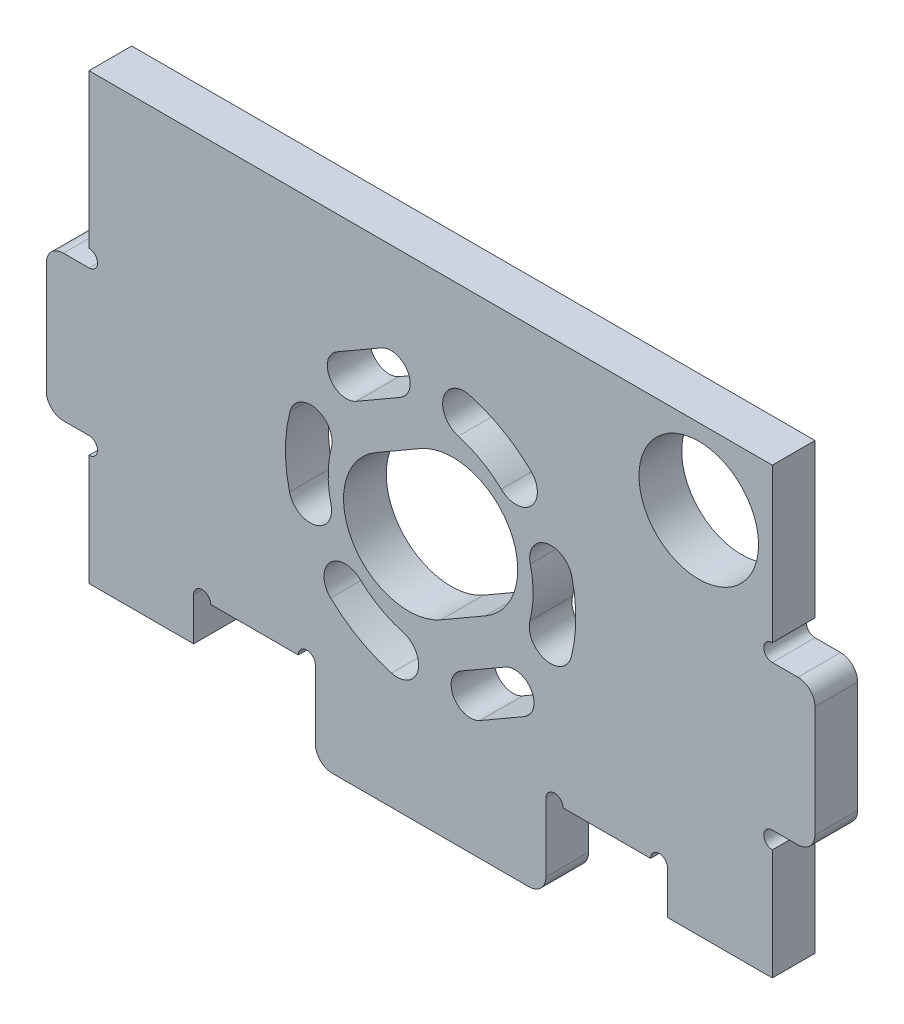
SolidWorks part; units mm, degrees
ref_plane "정면" through (0, 0, 0) normal (0, 0, 1) x (1, 0, 0)
ref_plane "윗면" through (0, 0, 0) normal (0, 1, 0) x (1, 0, 0)
ref_plane "우측면" through (0, 0, 0) normal (1, 0, 0) x (0, 0, -1)
sketch "스케치1" plane through (0, 0, 0) normal (0, 0, 1) x (1, 0, 0)
  line L0 (-5.1962, 22.5) -> (0, 25.5) construction
  line L1 (-42.5981, 51) -> (37.4019, 51)
  line L2 (-42.5981, 51) -> (-42.5981, -1)
  line L3 (-42.5981, -1) -> (37.4019, -1)
  line L4 (37.4019, 51) -> (37.4019, -1)
  line L5 (-8.9962, 29.0818) -> (-3.8, 32.0818)
  line L6 (-1.3962, 15.9182) -> (3.8, 18.9182)
  line L7 (-9.8481, 36.5574) -> (-2.5981, 24) construction
  line L8 (-2.5981, 24) -> (4.6519, 11.4426) construction
  line L9 (-2.5981, 24) -> (4.6519, 36.5574) construction
  line L10 (-2.5981, 24) -> (11.9019, 24) construction
  line L11 (-2.5981, 24) -> (9.9593, 31.25) construction
  arc A0 (-8.9962, 29.0818) -> (-1.3962, 15.9182) centre (-5.1962, 22.5) ccw
  circle A1 centre (-2.5981, 24) radius 14.5 construction
  arc A2 (1.3092, 37.9636) -> (7.3956, 34.506) centre (-2.5981, 24) cw construction
  arc A3 (3.8, 18.9182) -> (-3.8, 32.0818) centre (0, 25.5) ccw
  arc A4 (9.1187, 36.3174) -> (1.9829, 40.3712) centre (-2.5981, 24) ccw
  arc A5 (5.6726, 32.6946) -> (0.6355, 35.5561) centre (-2.5981, 24) ccw
  arc A6 (5.6726, 32.6946) -> (9.1187, 36.3174) centre (7.3956, 34.506) ccw
  arc A7 (1.9829, 40.3712) -> (0.6355, 35.5561) centre (1.3092, 37.9636) ccw
  arc A8 (11.4484, 20.402) -> (11.4972, 27.4018) centre (-2.5981, 24) ccw construction
  arc A9 (13.9275, 27.9883) -> (13.8702, 19.7816) centre (-2.5981, 24) cw
  arc A10 (9.067, 26.8153) -> (9.0266, 21.0223) centre (-2.5981, 24) cw
  arc A11 (9.067, 26.8153) -> (13.9275, 27.9883) centre (11.4972, 27.4018) cw
  arc A12 (13.8702, 19.7816) -> (9.0266, 21.0223) centre (11.4484, 20.402) cw
  arc A13 (-6.5053, 10.0364) -> (-12.5918, 13.494) centre (-2.5981, 24) cw construction
  arc A14 (-14.3148, 11.6826) -> (-7.179, 7.6288) centre (-2.5981, 24) ccw
  arc A15 (-10.8687, 15.3054) -> (-5.8317, 12.4439) centre (-2.5981, 24) ccw
  arc A16 (-10.8687, 15.3054) -> (-14.3148, 11.6826) centre (-12.5918, 13.494) ccw
  arc A17 (-7.179, 7.6288) -> (-5.8317, 12.4439) centre (-6.5053, 10.0364) ccw
  arc A18 (-16.6446, 27.598) -> (-16.6934, 20.5982) centre (-2.5981, 24) ccw construction
  arc A19 (-19.1236, 20.0117) -> (-19.0664, 28.2184) centre (-2.5981, 24) cw
  arc A20 (-14.2632, 21.1847) -> (-14.2228, 26.9777) centre (-2.5981, 24) cw
  arc A21 (-14.2632, 21.1847) -> (-19.1236, 20.0117) centre (-16.6934, 20.5982) cw
  arc A22 (-19.0664, 28.2184) -> (-14.2228, 26.9777) centre (-16.6446, 27.598) cw
  point P3 (-2.5981, 24)
  point P20 (4.5642, 36.6076)
  point P28 (11.9016, 23.8989)
  point P35 (-9.7603, 11.3924)
  point P42 (-17.0977, 24.1011)
  dimension "D1" = 30
  dimension "D2" = 40
  dimension "D8" = 7.6
  dimension "D5" = 29
  dimension "D11" = 2.5
  dimension "D3" = 80
  dimension "D4" = 52
  dimension "D6" = 60
  dimension "D7" = 6
  dimension "D9" = 25
  dimension "D10" = 60
  dimension "D12" = 7
extrude "보스-돌출1" add sketch "스케치1" along normal blind 5
sketch "스케치2" plane through (0, 0, 5) normal (0, 0, 1) x (1, 0, 0)
  line L0 (4.6519, 11.4426) -> (-2.5981, 24) construction
  line L1 (-2.5981, 24) -> (-9.8481, 36.5574) construction
  line L8 (6.5818, 29.3) -> (-2.5981, 24) construction
  line L9 (-2.5981, 24) -> (-11.7779, 18.7) construction
  line L10 (7.25, 12.9426) -> (2.0538, 9.9426) construction
  line L11 (8.375, 10.9941) -> (3.1788, 7.9941)
  line L12 (6.125, 14.8912) -> (0.9288, 11.8912)
  line L13 (-7.25, 38.0574) -> (-12.4462, 35.0574) construction
  line L14 (-6.125, 36.1088) -> (-11.3212, 33.1088)
  line L15 (-8.375, 40.0059) -> (-13.5712, 37.0059)
  arc A4 (3.8, 18.9182) -> (-3.8, 32.0818) centre (0, 25.5) ccw construction
  arc A5 (-8.9962, 29.0818) -> (-1.3962, 15.9182) centre (-5.1962, 22.5) ccw construction
  arc A8 (8.375, 10.9941) -> (6.125, 14.8912) centre (7.25, 12.9426) ccw
  arc A9 (0.9288, 11.8912) -> (3.1788, 7.9941) centre (2.0538, 9.9426) ccw
  arc A10 (-6.125, 36.1088) -> (-8.375, 40.0059) centre (-7.25, 38.0574) ccw
  arc A11 (-13.5712, 37.0059) -> (-11.3212, 33.1088) centre (-12.4462, 35.0574) ccw
  point P28 (4.6519, 11.4426)
  point P34 (-9.8481, 36.5574)
  dimension "D2" = 6
  dimension "D3" = 2.25
  dimension "D4" = 2.25
  dimension "D1" = 29
extrude "컷-돌출1" cut sketch "스케치2" against normal blind 5
sketch "스케치3" plane through (0, 0, 5) normal (0, 0, 1) x (1, 0, 0)
  line L0 (-2.5981, 24) -> (28.7953, 42.125) construction
  line L1 (6.5818, 29.3) -> (-2.5981, 24) construction
  line L3 (-2.5981, 24) -> (-11.7779, 18.7) construction
  circle A0 centre (28.7953, 42.125) radius 7
  arc A1 (-8.9962, 29.0818) -> (-1.3962, 15.9182) centre (-5.1962, 22.5) ccw construction
  arc A2 (3.8, 18.9182) -> (-3.8, 32.0818) centre (0, 25.5) ccw construction
  dimension "D2" = 14
  dimension "D1" = 36.25
extrude "컷-돌출2" cut sketch "스케치3" against normal blind 10
sketch "스케치4" plane through (0, 0, 5) normal (0, 0, 1) x (1, 0, 0)
  line L0 (6.5818, 29.3) -> (-2.5981, 24) construction
  line L1 (-2.5981, 24) -> (-11.7779, 18.7) construction
  circle A0 centre (-2.5981, 24) radius 7.5
  arc A5 (3.8, 18.9182) -> (-3.8, 32.0818) centre (0, 25.5) ccw construction
  arc A6 (-8.9962, 29.0818) -> (-1.3962, 15.9182) centre (-5.1962, 22.5) ccw construction
sketch "스케치5" plane through (0, 0, 5) normal (0, 0, 1) x (1, 0, 0)
  line L0 (37.4019, -1) -> (37.4019, 51) construction
  line L1 (37.4019, 41) -> (42.4019, 41)
  line L2 (37.4019, 41) -> (37.4019, 31)
  line L3 (37.4019, 31) -> (42.4019, 31)
  line L4 (42.4019, 41) -> (42.4019, 31)
  line L5 (42.4019, 31) -> (42.4019, 19) construction
  line L6 (37.4019, 19) -> (42.4019, 19)
  line L7 (37.4019, 19) -> (37.4019, 9)
  line L8 (37.4019, 9) -> (42.4019, 9)
  line L9 (42.4019, 19) -> (42.4019, 9)
  line L10 (37.4019, 51) -> (-42.5981, 51) construction
  line L11 (-42.5981, -1) -> (37.4019, -1) construction
  line L12 (-2.5981, 51) -> (-2.5981, -1) construction
  line L13 (-47.5981, 19) -> (-47.5981, 9)
  line L14 (-42.5981, 9) -> (-47.5981, 9)
  line L15 (-42.5981, 19) -> (-42.5981, 9)
  line L16 (-42.5981, 19) -> (-47.5981, 19)
  line L17 (-47.5981, 41) -> (-47.5981, 31)
  line L18 (-42.5981, 31) -> (-47.5981, 31)
  line L19 (-42.5981, 41) -> (-42.5981, 31)
  line L20 (-42.5981, 41) -> (-47.5981, 41)
  dimension "D1" = 10
  dimension "D2" = 10
  dimension "D3" = 10
  dimension "D4" = 10
  dimension "D5" = 5
extrude "보스-돌출2" [suppressed] add sketch "스케치5" against normal blind 5
sketch "스케치6" [suppressed] plane through (0, 0, 5) normal (0, 0, 1) x (1, 0, 0)
  line L0 (27.4019, 41) -> (22.4019, 41) construction
  line L1 (22.4019, 31) -> (27.4019, 31) construction
  line L2 (27.4019, 19) -> (22.4019, 19) construction
  line L3 (22.4019, 9) -> (27.4019, 9) construction
  line L4 (-10.0981, 51) -> (-10.0981, -1) construction
  line L5 (22.4019, 51) -> (-42.5981, 51) construction
  line L6 (-42.5981, -1) -> (22.4019, -1) construction
  circle A0 centre (23.4019, 41) radius 1
  circle A1 centre (23.4019, 31) radius 1
  circle A2 centre (23.4019, 19) radius 1
  circle A3 centre (23.4019, 9) radius 1
  circle A4 centre (-43.5981, 9) radius 1
  circle A5 centre (-43.5981, 19) radius 1
  circle A6 centre (-43.5981, 31) radius 1
  circle A7 centre (-43.5981, 41) radius 1
  dimension "D1" = 2
extrude "컷-돌출3" [suppressed] cut sketch "스케치6" against normal blind 5
sketch "스케치8" plane through (0, 0, 5) normal (0, 0, 1) x (1, 0, 0)
  line L0 (-42.5981, 30.55) -> (-36.5981, 30.55)
  line L1 (-42.5981, 30.55) -> (-42.5981, 27.45)
  line L2 (-42.5981, 27.45) -> (-36.5981, 27.45)
  line L3 (-32.5981, 30.55) -> (-32.5981, 27.45) construction
  line L4 (-33.7981, 27.45) -> (-32.5981, 27.45)
  line L5 (-36.5981, 30.55) -> (-36.5981, 31.75)
  line L6 (-36.5981, 31.75) -> (-33.7981, 31.75) construction
  line L7 (-33.7981, 31.75) -> (-33.7981, 30.55)
  line L8 (-33.7981, 27.45) -> (-33.7981, 26.25)
  line L9 (-33.7981, 26.25) -> (-36.5981, 26.25) construction
  line L10 (-33.7981, 30.55) -> (-32.5981, 30.55)
  line L11 (-36.5981, 26.25) -> (-36.5981, 27.45)
  line L12 (-36.5981, 30.55) -> (-36.5981, 27.45) construction
  line L13 (-33.7981, 30.55) -> (-33.7981, 27.45) construction
  line L14 (-36.5981, 27.45) -> (-33.7981, 27.45) construction
  line L15 (-33.7981, 30.55) -> (-36.5981, 30.55) construction
  line L16 (-26.4709, 29) -> (-32.5981, 29) construction
  line L17 (-42.5981, 10.55) -> (-36.5981, 10.55)
  line L18 (-42.5981, 10.55) -> (-42.5981, 7.45)
  line L19 (-42.5981, 7.45) -> (-36.5981, 7.45)
  line L20 (-32.5981, 10.55) -> (-32.5981, 7.45) construction
  line L21 (-33.7981, 7.45) -> (-32.5981, 7.45)
  line L22 (-36.5981, 10.55) -> (-36.5981, 11.75)
  line L23 (-36.5981, 11.75) -> (-33.7981, 11.75) construction
  line L24 (-33.7981, 11.75) -> (-33.7981, 10.55)
  line L25 (-33.7981, 7.45) -> (-33.7981, 6.25)
  line L26 (-33.7981, 6.25) -> (-36.5981, 6.25) construction
  line L27 (-33.7981, 10.55) -> (-32.5981, 10.55)
  line L28 (-36.5981, 6.25) -> (-36.5981, 7.45)
  line L29 (-36.5981, 10.55) -> (-36.5981, 7.45) construction
  line L30 (-33.7981, 10.55) -> (-33.7981, 7.45) construction
  line L31 (-36.5981, 7.45) -> (-33.7981, 7.45) construction
  line L32 (-33.7981, 10.55) -> (-36.5981, 10.55) construction
  line L33 (-26.4709, 9) -> (-32.5981, 9) construction
  line L34 (-26.4709, 29) -> (-26.4709, 9) construction
  line L35 (-42.5981, -1) -> (37.4019, -1) construction
  line L36 (-2.5981, 51) -> (-2.5981, -1) construction
  line L37 (37.4019, 51) -> (-42.5981, 51) construction
  line L38 (21.2747, 29) -> (21.2747, 9) construction
  line L39 (21.2747, 9) -> (27.4019, 9) construction
  line L40 (28.6019, 10.55) -> (31.4019, 10.55) construction
  line L41 (31.4019, 7.45) -> (28.6019, 7.45) construction
  line L42 (28.6019, 10.55) -> (28.6019, 7.45) construction
  line L43 (31.4019, 10.55) -> (31.4019, 7.45) construction
  line L44 (28.6019, 6.25) -> (31.4019, 6.25) construction
  line L45 (31.4019, 11.75) -> (28.6019, 11.75) construction
  line L46 (27.4019, 10.55) -> (27.4019, 7.45) construction
  line L47 (21.2747, 29) -> (27.4019, 29) construction
  line L48 (28.6019, 30.55) -> (31.4019, 30.55) construction
  line L49 (31.4019, 27.45) -> (28.6019, 27.45) construction
  line L50 (28.6019, 30.55) -> (28.6019, 27.45) construction
  line L51 (31.4019, 30.55) -> (31.4019, 27.45) construction
  line L52 (28.6019, 26.25) -> (31.4019, 26.25) construction
  line L53 (31.4019, 31.75) -> (28.6019, 31.75) construction
  line L54 (27.4019, 30.55) -> (27.4019, 27.45) construction
  line L55 (31.4019, 6.25) -> (31.4019, 7.45)
  line L56 (28.6019, 10.55) -> (27.4019, 10.55)
  line L57 (28.6019, 7.45) -> (28.6019, 6.25)
  line L58 (28.6019, 11.75) -> (28.6019, 10.55)
  line L59 (31.4019, 10.55) -> (31.4019, 11.75)
  line L60 (28.6019, 7.45) -> (27.4019, 7.45)
  line L61 (37.4019, 7.45) -> (31.4019, 7.45)
  line L62 (37.4019, 10.55) -> (37.4019, 7.45)
  line L63 (37.4019, 10.55) -> (31.4019, 10.55)
  line L64 (31.4019, 26.25) -> (31.4019, 27.45)
  line L65 (28.6019, 30.55) -> (27.4019, 30.55)
  line L66 (28.6019, 27.45) -> (28.6019, 26.25)
  line L67 (28.6019, 31.75) -> (28.6019, 30.55)
  line L68 (31.4019, 30.55) -> (31.4019, 31.75)
  line L69 (28.6019, 27.45) -> (27.4019, 27.45)
  line L70 (37.4019, 27.45) -> (31.4019, 27.45)
  line L71 (37.4019, 30.55) -> (37.4019, 27.45)
  line L72 (37.4019, 30.55) -> (31.4019, 30.55)
  arc A0 (-33.7981, 31.75) -> (-36.5981, 31.75) centre (-35.1981, 31.75) ccw
  arc A1 (-36.5981, 26.25) -> (-33.7981, 26.25) centre (-35.1981, 26.25) ccw
  arc A2 (-32.5981, 27.45) -> (-32.5981, 30.55) centre (-32.5981, 29) ccw
  arc A3 (-33.7981, 11.75) -> (-36.5981, 11.75) centre (-35.1981, 11.75) ccw
  arc A4 (-36.5981, 6.25) -> (-33.7981, 6.25) centre (-35.1981, 6.25) ccw
  arc A5 (-32.5981, 7.45) -> (-32.5981, 10.55) centre (-32.5981, 9) ccw
  arc A6 (27.4019, 7.45) -> (27.4019, 10.55) centre (27.4019, 9) cw
  arc A7 (31.4019, 6.25) -> (28.6019, 6.25) centre (30.0019, 6.25) cw
  arc A8 (28.6019, 11.75) -> (31.4019, 11.75) centre (30.0019, 11.75) cw
  arc A9 (27.4019, 27.45) -> (27.4019, 30.55) centre (27.4019, 29) cw
  arc A10 (31.4019, 26.25) -> (28.6019, 26.25) centre (30.0019, 26.25) cw
  arc A11 (28.6019, 31.75) -> (31.4019, 31.75) centre (30.0019, 31.75) cw
  dimension "D1" = 3.1
  dimension "D2" = 10
  dimension "D3" = 5.5
  dimension "D4" = 2.8
  dimension "D5" = 3.1
  dimension "D6" = 10
  dimension "D7" = 5.5
  dimension "D8" = 2.8
  dimension "D9" = 20
  dimension "D10" = 10
extrude "컷-돌출4" [suppressed] cut sketch "스케치8" against normal blind 10
sketch "스케치10" plane through (0, 0, 5) normal (0, 0, 1) x (1, 0, 0)
  line L0 (10.9019, -6) -> (37.4019, -6) construction
  line L1 (-16.0981, -1) -> (10.9019, -1)
  line L2 (37.4019, -1) -> (37.4019, 51) construction
  line L3 (37.4019, 31) -> (42.4019, 31)
  line L4 (37.4019, 31) -> (37.4019, 14)
  line L5 (-16.0981, -1) -> (-16.0981, -6)
  line L6 (37.4019, 14) -> (42.4019, 14)
  line L7 (42.4019, 31) -> (42.4019, 14)
  line L8 (-42.5981, 51) -> (-42.5981, -1) construction
  line L9 (-42.5981, 31) -> (-47.5981, 31)
  line L10 (-42.5981, 31) -> (-42.5981, 14)
  line L11 (-16.0981, -6) -> (10.9019, -6)
  line L12 (-42.5981, 14) -> (-47.5981, 14)
  line L13 (-47.5981, 31) -> (-47.5981, 14)
  line L14 (37.4019, 51) -> (-42.5981, 51) construction
  line L15 (-42.5981, -1) -> (37.4019, -1) construction
  line L16 (10.9019, -1) -> (10.9019, -6)
  line L17 (37.4019, -6) -> (37.4019, -1) construction
  line L18 (-16.0981, -6) -> (-42.5981, -6) construction
  line L19 (-42.5981, -6) -> (-42.5981, -1) construction
  dimension "D1" = 5
  dimension "D2" = 20
  dimension "D3" = 15
  dimension "D4" = 27
  dimension "D5" = 5
extrude "보스-돌출3" add sketch "스케치10" against normal blind 5
sketch "스케치11" plane through (0, 0, 5) normal (0, 0, 1) x (1, 0, 0)
  line L0 (37.4019, 31) -> (37.4019, 51) construction
  line L1 (37.4019, -1) -> (37.4019, 14) construction
  line L2 (-42.5981, 14) -> (-42.5981, -1) construction
  line L3 (-42.5981, 51) -> (-42.5981, 31) construction
  line L4 (10.9019, -1) -> (37.4019, -1) construction
  line L5 (-42.5981, -1) -> (-16.0981, -1) construction
  circle A0 centre (37.4019, 32) radius 1
  circle A1 centre (37.4019, 13) radius 1
  circle A2 centre (-42.5981, 13) radius 1
  circle A3 centre (-42.5981, 32) radius 1
  circle A4 centre (11.9019, -1) radius 1
  circle A5 centre (-17.0981, -1) radius 1
  dimension "D1" = 2
extrude "컷-돌출5" cut sketch "스케치11" against normal blind 5
fillet "필렛1" radius 2 6 edges at (42.4019, 31, 2.5) (42.4019, 14, 2.5) (10.9019, -6, 2.5) (-16.0981, -6, 2.5) (-47.5981, 14, 2.5) (-47.5981, 31, 2.5)
sketch "스케치12" plane through (0, 0, 5) normal (0, 0, 1) x (1, 0, 0)
  line L0 (12.9019, -1) -> (37.4019, -1) construction
  line L1 (25.1519, -1) -> (10.9019, -1)
  line L2 (25.1519, -1) -> (25.1519, 4)
  line L3 (25.1519, 4) -> (10.9019, 4)
  line L4 (10.9019, -1) -> (10.9019, 4)
  line L5 (-42.5981, -1) -> (-18.0981, -1) construction
  line L6 (-30.3481, -1) -> (-16.0981, -1)
  line L7 (-30.3481, -1) -> (-30.3481, 4)
  line L8 (-30.3481, 4) -> (-16.0981, 4)
  line L9 (-16.0981, -1) -> (-16.0981, 4)
  line L10 (10.9019, -4) -> (10.9019, -1) construction
  dimension "D1" = 5
extrude "컷-돌출6" cut sketch "스케치12" against normal blind 10
sketch "스케치15" plane through (0, 0, 5) normal (0, 0, 1) x (1, 0, 0)
  line L0 (25.1519, 4) -> (10.9019, 4) construction
  line L1 (-16.0981, 4) -> (-30.3481, 4) construction
  circle A0 centre (11.9019, 4) radius 1
  circle A1 centre (24.1519, 4) radius 1
  circle A2 centre (-17.0981, 4) radius 1
  circle A3 centre (-29.3481, 4) radius 1
  dimension "D1" = 2
extrude "컷-돌출7" cut sketch "스케치15" against normal blind 10
